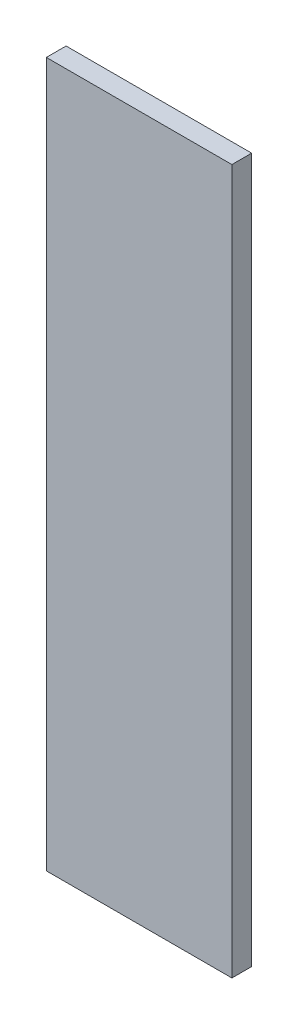
SolidWorks part; units mm, degrees
ref_plane "Front Plane" through (0, 0, 0) normal (1, 0, 0) x (0, 1, 0)
ref_plane "Top Plane" through (0, 0, 0) normal (0, 0, 1) x (0, 1, 0)
ref_plane "Right Plane" through (0, 0, 0) normal (0, 1, 0) x (-1, 0, 0)
sketch "Sketch1" plane through (0, 0, 0) normal (0, 0, 1) x (0, 1, 0)
  line L1 (-20.5, 5.4) -> (20.5, 5.4)
  line L2 (-20.5, 5.4) -> (-20.5, -5.4)
  line L3 (-20.5, -5.4) -> (20.5, -5.4)
  line L4 (20.5, 5.4) -> (20.5, -5.4)
  line L5 (-20.5, 5.4) -> (20.5, -5.4) construction
  line L6 (-20.5, -5.4) -> (20.5, 5.4) construction
  point P0 (0, 0)
  dimension "D1" = 10.8
  dimension "D2" = 41
extrude "Boss-Extrude1" add sketch "Sketch1" along normal blind 1.15
